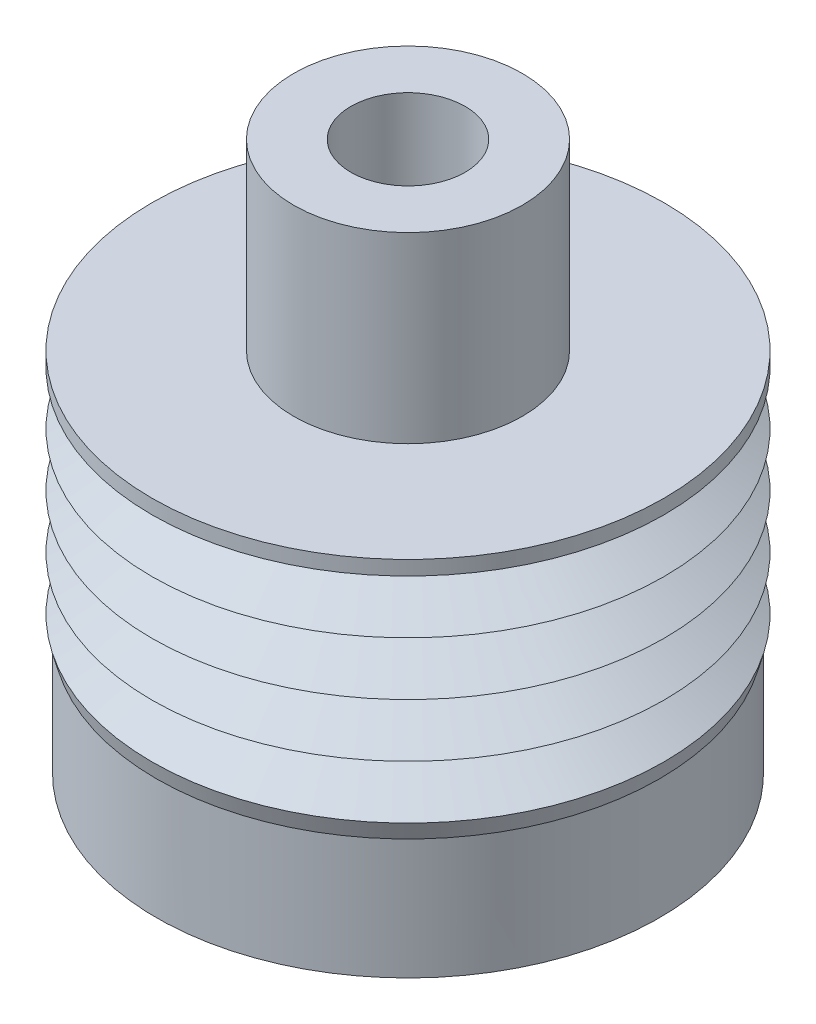
SolidWorks part; units mm, degrees
material "Liga 6061"
ref_plane "Plano frontal" through (0, 0, 0) normal (0, 0, 1) x (1, 0, 0)
ref_plane "Plano superior" through (0, 0, 0) normal (0, 1, 0) x (1, 0, 0)
ref_plane "Plano direito" through (0, 0, 0) normal (1, 0, 0) x (0, 0, -1)
sketch "Esboço1" plane through (0, 0, 0) normal (0, 0, 1) x (1, 0, 0)
  line L0 (0, 0) -> (0, 69.8379) construction
  line L1 (0, 0) -> (49.0685, 0) construction
  line L2 (11, 0) -> (11, 5.8945)
  line L3 (2.5, 0) -> (2.5, 16)
  line L4 (2.5, 16) -> (11.2, 16)
  line L5 (11.2, 15.37) -> (9.1735, 14.2)
  line L6 (9.1735, 14.2) -> (11.2, 13.03)
  line L7 (11.2, 16) -> (11.2, 15.37)
  line L8 (11.2, 13.03) -> (9.1735, 11.86)
  line L9 (9.1735, 11.86) -> (11.2, 10.69)
  line L10 (11.2, 10.69) -> (9.1735, 9.52)
  line L11 (9.1735, 9.52) -> (11.2, 8.35)
  line L12 (11.2, 8.35) -> (9.1735, 7.18)
  line L13 (9.1735, 7.18) -> (11.2, 6.01)
  line L18 (11.2, 6.01) -> (11, 5.8945)
  line L19 (2.5, 0) -> (11, 0)
  line L20 (9.1735, 2.5) -> (11.2, 1.33) [skipped]
  line L21 (11.2, 3.67) -> (9.1735, 2.5) [skipped]
  line L22 (9.1735, 4.84) -> (11.2, 3.67) [skipped]
  line L23 (11.2, 6.01) -> (9.1735, 4.84) [skipped]
  point P11 (11.2, 14.01)
  point P12 (11.2, 10.0112)
  point P16 (11.2, 9.3491)
  dimension "D1" = 5
  dimension "D2" = 1.8
  dimension "D3" = 11
  dimension "D4" = 60
  dimension "D5" = 11.2
  dimension "D6" = 2.34
  dimension "D7" = 120
  dimension "D9" = 16
  dimension "D10" = 60
  dimension "D8" = 6
revolve "Revolução1" add sketch "Esboço1" angle 360 about L0
chamfer "Chanfro1" distance 0.23 angle 45 1 edges at (0, 5.8945, -11)
sketch "Esboço2" plane through (0, 16, 0) normal (0, 1, 0) x (1, 0, 0)
  circle A0 centre (0, 0) radius 5
  circle A1 centre (0, 0) radius 2.5
  dimension "D1" = 10
  dimension "D2" = 5
extrude "Ressalto-extrusão1" add sketch "Esboço2" along normal blind 8
